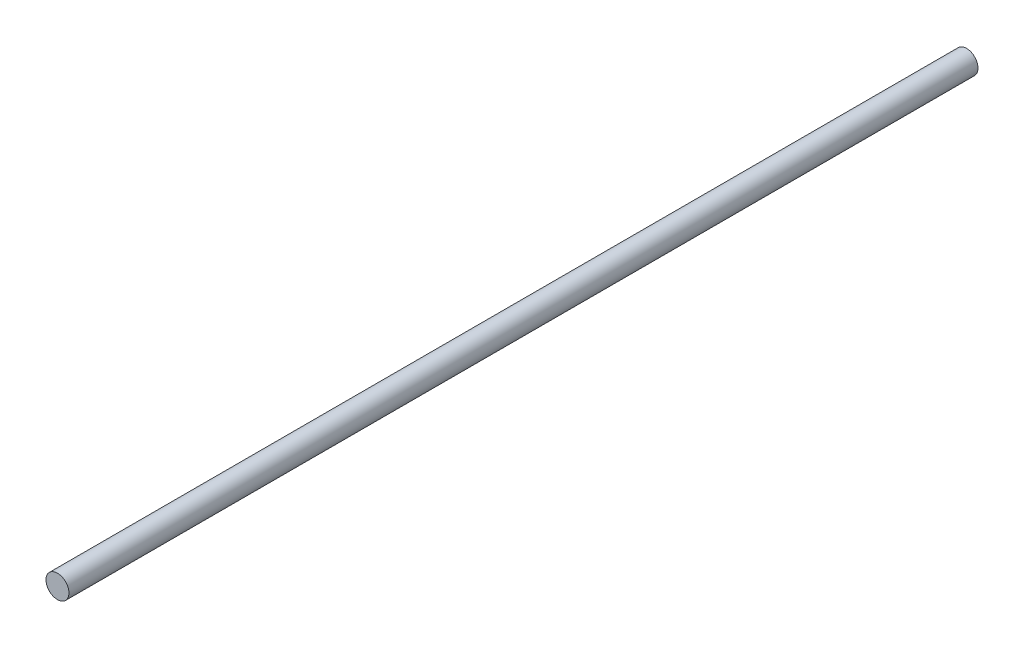
SolidWorks part; units mm, degrees
material "6061 Alloy"
ref_plane "Front Plane" through (0, 0, 0) normal (0, 0, 1) x (1, 0, 0)
ref_plane "Top Plane" through (0, 0, 0) normal (0, 1, 0) x (1, 0, 0)
ref_plane "Right Plane" through (0, 0, 0) normal (1, 0, 0) x (0, 0, -1)
sketch "Sketch1" plane through (0, 0, 0) normal (0, 0, 1) x (1, 0, 0)
  circle A0 centre (0, 0) radius 3.175
  dimension "D1" = 6.35
extrude "Boss-Extrude1" add sketch "Sketch1" against normal blind 251.46
